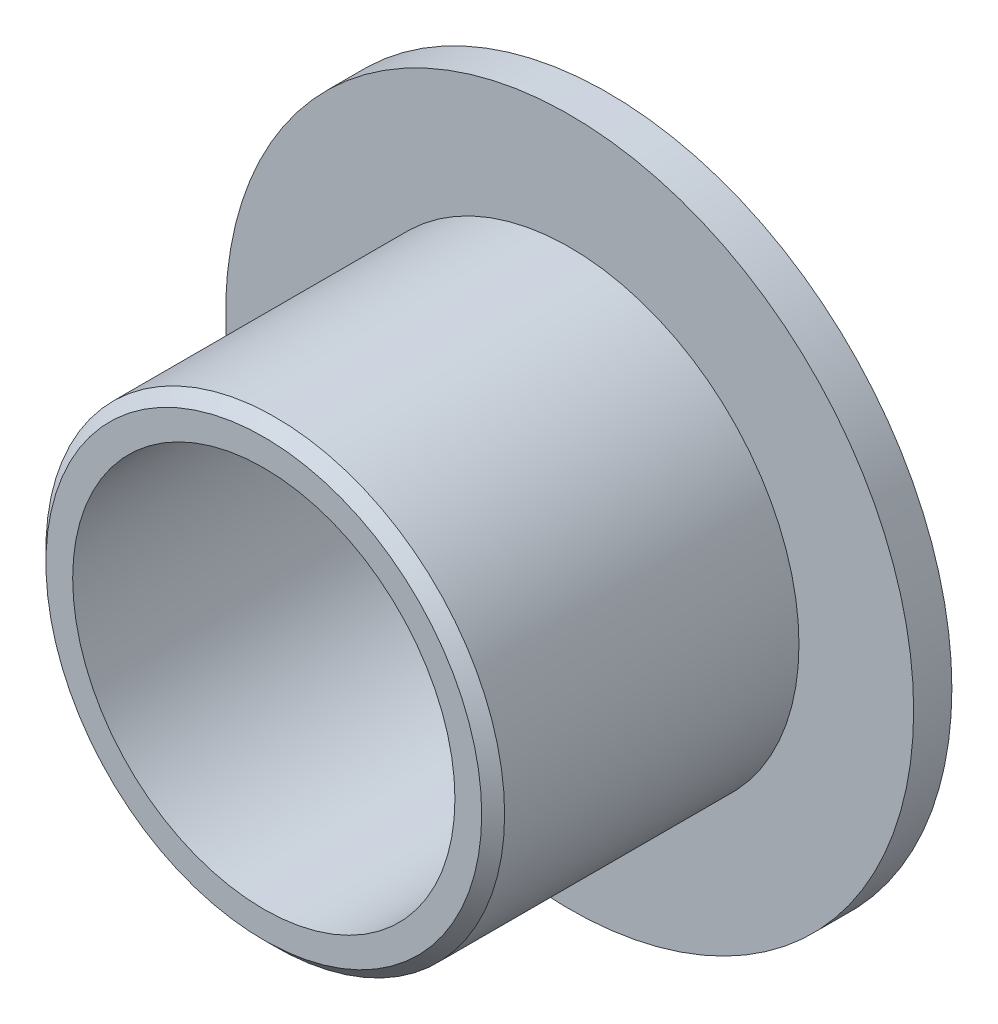
SolidWorks part; units mm, degrees
ref_plane "Płaszczyzna przednia" through (0, 0, 0) normal (0, 0, 1) x (1, 0, 0)
ref_plane "Płaszczyzna górna" through (0, 0, 0) normal (0, 1, 0) x (1, 0, 0)
ref_plane "Płaszczyzna prawa" through (0, 0, 0) normal (1, 0, 0) x (0, 0, -1)
sketch "Sketch1" plane through (0, 0, 0) normal (0, 0, 1) x (1, 0, 0)
  circle A0 centre (0, 0) radius 9
  circle A1 centre (0, 0) radius 5
  dimension "D1" = 18
  dimension "D2" = 10
extrude "Boss-Extrude1" add sketch "Sketch1" along normal blind 1
sketch "Sketch2" plane through (0, 0, 1) normal (0, 0, 1) x (1, 0, 0)
  circle A0 centre (0, 0) radius 5
  circle A1 centre (0, 0) radius 5 construction
  circle A2 centre (0, 0) radius 6
  dimension "D1" = 1
extrude "Boss-Extrude2" add sketch "Sketch2" along normal blind 8
chamfer "Chamfer1" distance 0.3 angle 45 1 edges at (6, 0, 9)
